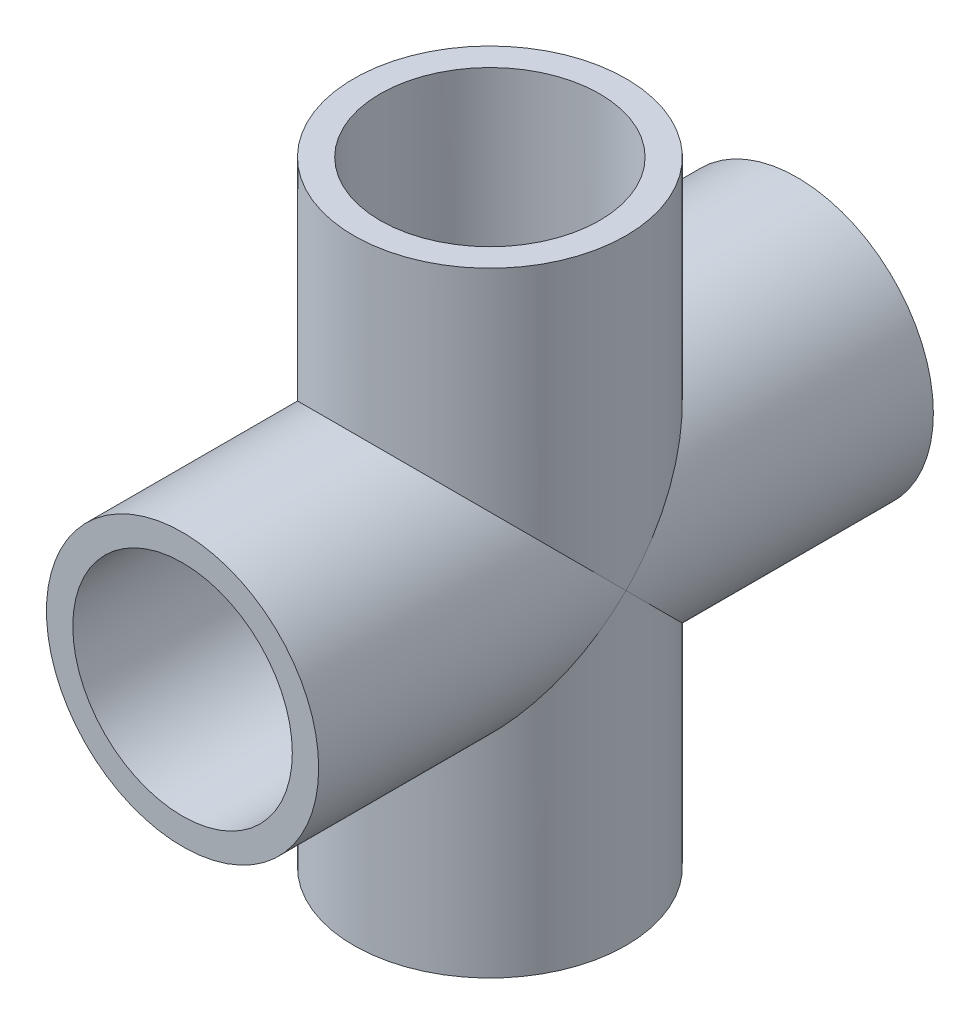
SolidWorks part; units mm, degrees
ref_plane "Front Plane" through (0, 0, 0) normal (0, 0, 1) x (1, 0, 0)
ref_plane "Top Plane" through (0, 0, 0) normal (0, 1, 0) x (1, 0, 0)
ref_plane "Right Plane" through (0, 0, 0) normal (1, 0, 0) x (0, 0, -1)
sketch "Sketch1" plane through (0, 0, 0) normal (0, 0, 1) x (1, 0, 0)
  circle A0 centre (0, 0) radius 12.5
  dimension "D1" = 25
extrude "Extrude-Thin1" add sketch "Sketch1" along normal mid plane 70 thin
sketch "Sketch2" plane through (0, 0, 0) normal (0, 1, 0) x (1, 0, 0)
  circle A0 centre (0, 0) radius 12.5
  dimension "D1" = 25
extrude "Extrude-Thin2" add sketch "Sketch2" along normal mid plane 70 thin
scale "Scale1" scale about centroid uniform scaling yes scale factor 0.5
